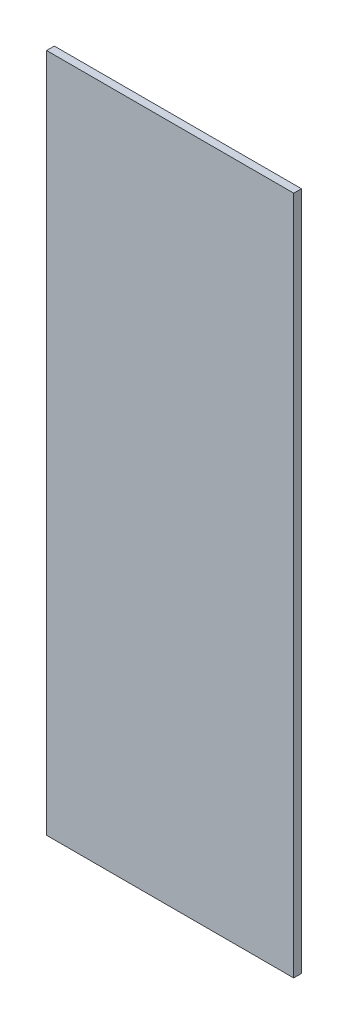
SolidWorks part; units mm, degrees
ref_plane "前视基准面" through (0, 0, 0) normal (0, 0, 1) x (1, 0, 0)
ref_plane "上视基准面" through (0, 0, 0) normal (0, 1, 0) x (1, 0, 0)
ref_plane "右视基准面" through (0, 0, 0) normal (1, 0, 0) x (0, 0, -1)
other "Configuration Table"
sketch "草图1" plane through (0, 0, 0) normal (0, 0, 1) x (1, 0, 0)
  line L1 (-40, 110) -> (40, 110)
  line L2 (-40, 110) -> (-40, -110)
  line L3 (-40, -110) -> (40, -110)
  line L4 (40, 110) -> (40, -110)
  line L5 (-40, 110) -> (40, -110) construction
  line L6 (-40, -110) -> (40, 110) construction
  point P0 (0, 0)
  dimension "D1" = 80
  dimension "D2" = 220
extrude "凸台-拉伸1" add sketch "草图1" along normal blind 2.5
